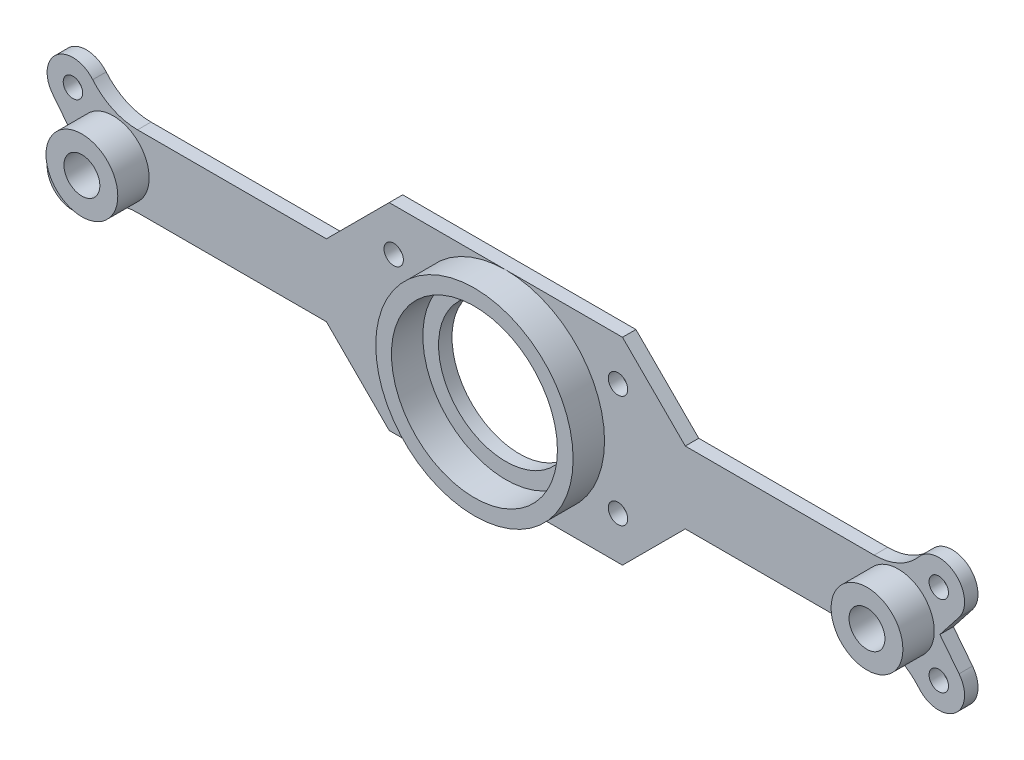
SolidWorks part; units mm, degrees
ref_plane "Front" through (0, 0, 0) normal (0, 0, 1) x (1, 0, 0)
ref_plane "Top" through (0, 0, 0) normal (0, 1, 0) x (1, 0, 0)
ref_plane "Right" through (0, 0, 0) normal (1, 0, 0) x (0, 0, -1)
sketch "Sketch1" plane through (0, 0, 0) normal (0, 0, 1) x (1, 0, 0)
  line L1 (-102.25, -31.25) -> (102.25, -31.25)
  line L2 (-102.25, -31.25) -> (-102.25, 31.25)
  line L3 (-102.25, 31.25) -> (102.25, 31.25)
  line L4 (102.25, -31.25) -> (102.25, 31.25)
  line L5 (-102.25, -31.25) -> (102.25, 31.25) construction
  line L6 (-102.25, 31.25) -> (102.25, -31.25) construction
  point P0 (0, 0)
  dimension "D1" = 204.5
  dimension "D2" = 62.5
extrude "Boss-Extrude1" add sketch "Sketch1" along normal blind 3
sketch "Sketch2" plane through (0, 0, 3) normal (0, 0, 1) x (1, 0, 0)
  line L0 (-87.5, 0) -> (87.5, 0) construction
  circle A0 centre (-87.5, 0) radius 8
  circle A1 centre (87.5, 0) radius 8
  point P4 (0, 0)
  dimension "D2" = 16
  dimension "D1" = 175
extrude "Boss-Extrude2" add sketch "Sketch2" along normal blind 7
sketch "Sketch3" plane through (0, 0, 3) normal (0, 0, 1) x (1, 0, 0)
  circle A0 centre (0, 0) radius 22
  dimension "D1" = 44
extrude "Boss-Extrude3" add sketch "Sketch3" along normal blind 7
sketch "Sketch4" plane through (0, 0, 3) normal (0, 0, 1) x (1, 0, 0)
  line L0 (-96.5, 9) -> (-96.5, -9) construction
  circle A0 centre (-96.5, 9) radius 2.165
  circle A1 centre (-96.5, -9) radius 2.165
  point P2 (-96.5, 0)
  dimension "D2" = 4.33
  dimension "D1" = 96.5
  dimension "D3" = 18
extrude "Cut-Extrude1" cut sketch "Sketch4" against normal through all
sketch "Sketch5" plane through (0, 0, 3) normal (0, 0, 1) x (1, 0, 0)
  line L0 (0, 26.875) -> (0, -26.875) construction
  circle A0 centre (0, 26.875) radius 2.165
  circle A1 centre (0, -26.875) radius 2.165
  point P3 (0, 0)
  dimension "D2" = 4.33
  dimension "D1" = 53.75
extrude "Cut-Extrude2" [suppressed] cut sketch "Sketch5" against normal through all
sketch "Sketch6" plane through (0, 0, 3) normal (0, 0, 1) x (1, 0, 0)
  line L0 (-82.093, -8) -> (-40, -8)
  line L1 (-40, -8) -> (-26, -22)
  line L2 (0, -31.25) -> (0, 0) construction
  line L3 (-102.25, -31.25) -> (102.25, -31.25) construction
  line L4 (-102.25, 31.25) -> (-102.25, -31.25) construction
  line L5 (0, -31.25) -> (-102.25, -31.25)
  line L6 (-102.25, -31.25) -> (-102.25, -9)
  line L7 (-102.25, 0) -> (-96.75, 0)
  line L8 (-96.75, 0) -> (-101.0249, -5.4521)
  line L9 (-102.25, 0) -> (-102.25, -9)
  line L10 (0, -22) -> (-26, -22)
  line L11 (0, -22) -> (0, -31.25)
  circle A0 centre (0, 0) radius 22 construction
  arc A1 (-101.0249, -5.4521) -> (-92.0818, -12.68) centre (-96.5, -9) ccw
  arc A3 (-82.093, -8) -> (-92.0818, -12.68) centre (-82.093, -21) ccw
  dimension "D5" = 13
  dimension "D1" = 45
  dimension "D2" = 8
  dimension "D3" = 40
  dimension "D6" = 5.5
extrude "Cut-Extrude3" cut sketch "Sketch6" against normal blind 7
mirror "Mirror1" about plane through (0, 0, 0) normal (1, 0, 0) of "Cut-Extrude1", "Cut-Extrude3"
mirror "Mirror2" about plane through (0, 0, 0) normal (0, 1, 0) of "Mirror1", "Cut-Extrude3"
sketch "Sketch7" plane through (0, 0, 10) normal (0, 0, 1) x (1, 0, 0)
  circle A0 centre (0, 0) radius 18.5
  dimension "D1" = 37
extrude "Cut-Extrude4" cut sketch "Sketch7" against normal blind 7
sketch "Sketch11" plane through (0, 0, 10) normal (0, 0, 1) x (1, 0, 0)
  circle A0 centre (-87.5, 0) radius 4
  circle A1 centre (87.5, 0) radius 4
  dimension "D1" = 8
extrude "Cut-Extrude7" cut sketch "Sketch11" against normal blind 7
sketch "Sketch12" plane through (0, 0, 3) normal (0, 0, 1) x (1, 0, 0)
  circle A0 centre (0, 0) radius 15
  dimension "D1" = 30
extrude "Cut-Extrude8" cut sketch "Sketch12" against normal through all
sketch "Sketch13" plane through (0, 0, 3) normal (0, 0, 1) x (1, 0, 0)
  line L1 (-25, 12.5) -> (25, 12.5) construction
  line L2 (-25, 12.5) -> (-25, -12.5) construction
  line L3 (-25, -12.5) -> (25, -12.5) construction
  line L4 (25, 12.5) -> (25, -12.5) construction
  line L5 (-25, 12.5) -> (25, -12.5) construction
  line L6 (-25, -12.5) -> (25, 12.5) construction
  circle A0 centre (-25, 12.5) radius 2.165
  circle A1 centre (-25, -12.5) radius 2.165
  circle A2 centre (25, -12.5) radius 2.165
  circle A3 centre (25, 12.5) radius 2.165
  point P0 (0, 0)
  dimension "D3" = 4.33
  dimension "D1" = 25
  dimension "D2" = 50
extrude "Cut-Extrude9" cut sketch "Sketch13" against normal through all
